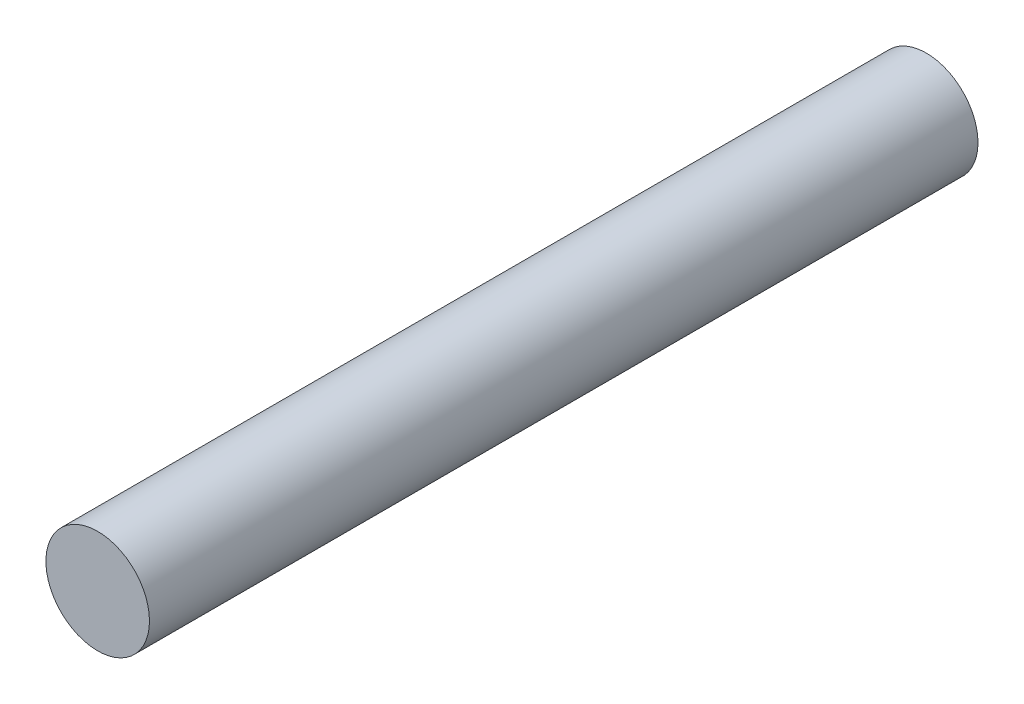
SolidWorks part; units mm, degrees
ref_plane "Front Plane" through (0, 0, 0) normal (1, 0, 0) x (0, 1, 0)
ref_plane "Top Plane" through (0, 0, 0) normal (0, 0, 1) x (0, 1, 0)
ref_plane "Right Plane" through (0, 0, 0) normal (0, 1, 0) x (-1, 0, 0)
sketch "Sketch1" plane through (0, 0, 0) normal (0, 0, 1) x (0, 1, 0)
  circle A0 centre (0, 0) radius 2.5
  dimension "D1" = 5
extrude "Boss-Extrude1" add sketch "Sketch1" along normal blind 40
